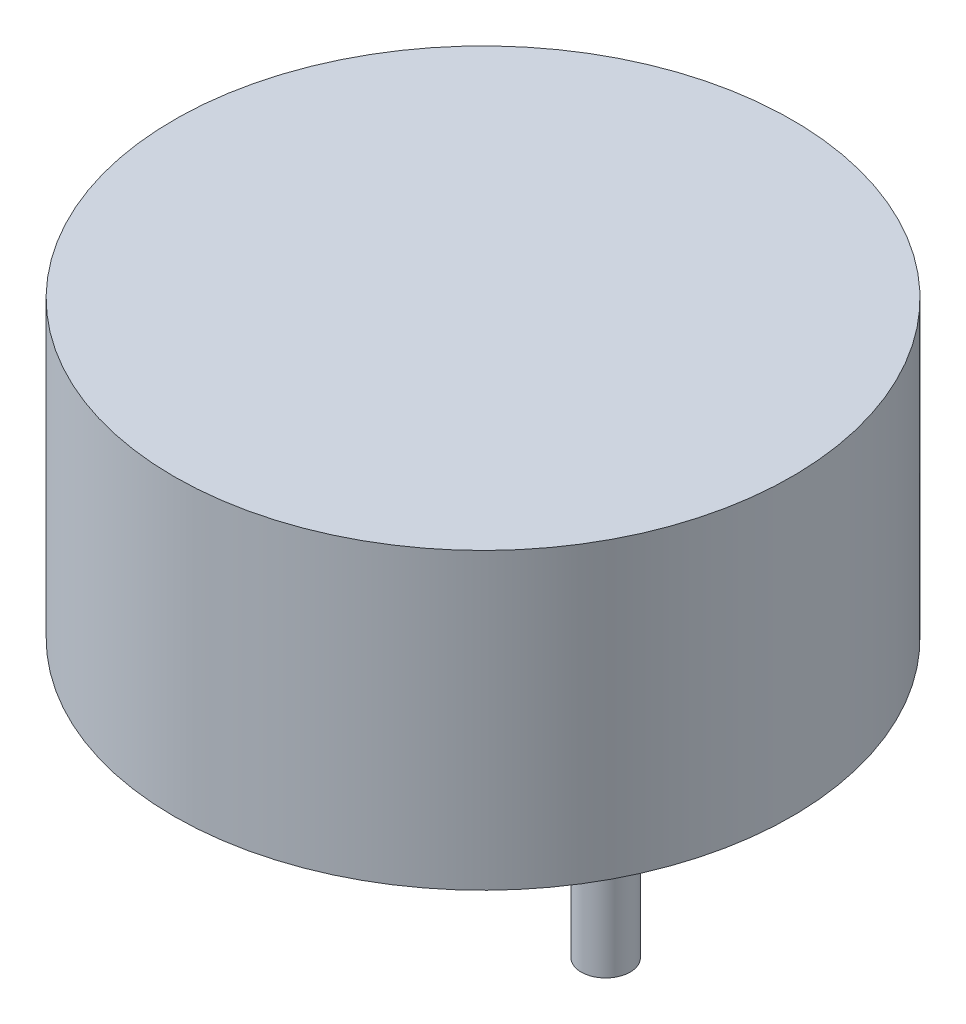
SolidWorks part; units mm, degrees
material "Buzzer"
ref_plane "Front Plane" through (0, 0, 0) normal (0, 0, 1) x (1, 0, 0)
ref_plane "Top Plane" through (0, 0, 0) normal (0, 1, 0) x (1, 0, 0)
ref_plane "Right Plane" through (0, 0, 0) normal (1, 0, 0) x (0, 0, -1)
sketch "Sketch1" plane through (0, 0, 0) normal (0, 1, 0) x (1, 0, 0)
  circle A0 centre (0, 0) radius 6.3
  dimension "D1" = 12.6
extrude "Boss-Extrude1" add sketch "Sketch1" along normal blind 6
sketch "Sketch2" plane through (0, 0, 0) normal (0, -1, 0) x (1, 0, 0)
  line L0 (0, 0) -> (0, 6.3) construction
  line L1 (0, 0) -> (0, -6.3) construction
  circle A0 centre (0, 0) radius 6.3 construction
  circle A1 centre (2.5, 0) radius 1.25
  dimension "D1" = 2.5
extrude "Boss-Extrude2" add sketch "Sketch2" along normal blind 0.9
sketch "Sketch3" plane through (0, -0.9, 0) normal (0, -1, 0) x (1, 0, 0)
  circle A0 centre (2.5, 0) radius 0.5
extrude "Boss-Extrude3" add sketch "Sketch3" along normal blind 3.5
mirror "Mirror1" about plane through (0, 0, 0) normal (1, 0, 0) of "Boss-Extrude3", "Boss-Extrude2"
sketch "Sketch4" plane through (0, 6, 0) normal (0, 1, 0) x (1, 0, 0)
  text T0 "PIEZO" font "Century Gothic" height 3.175
